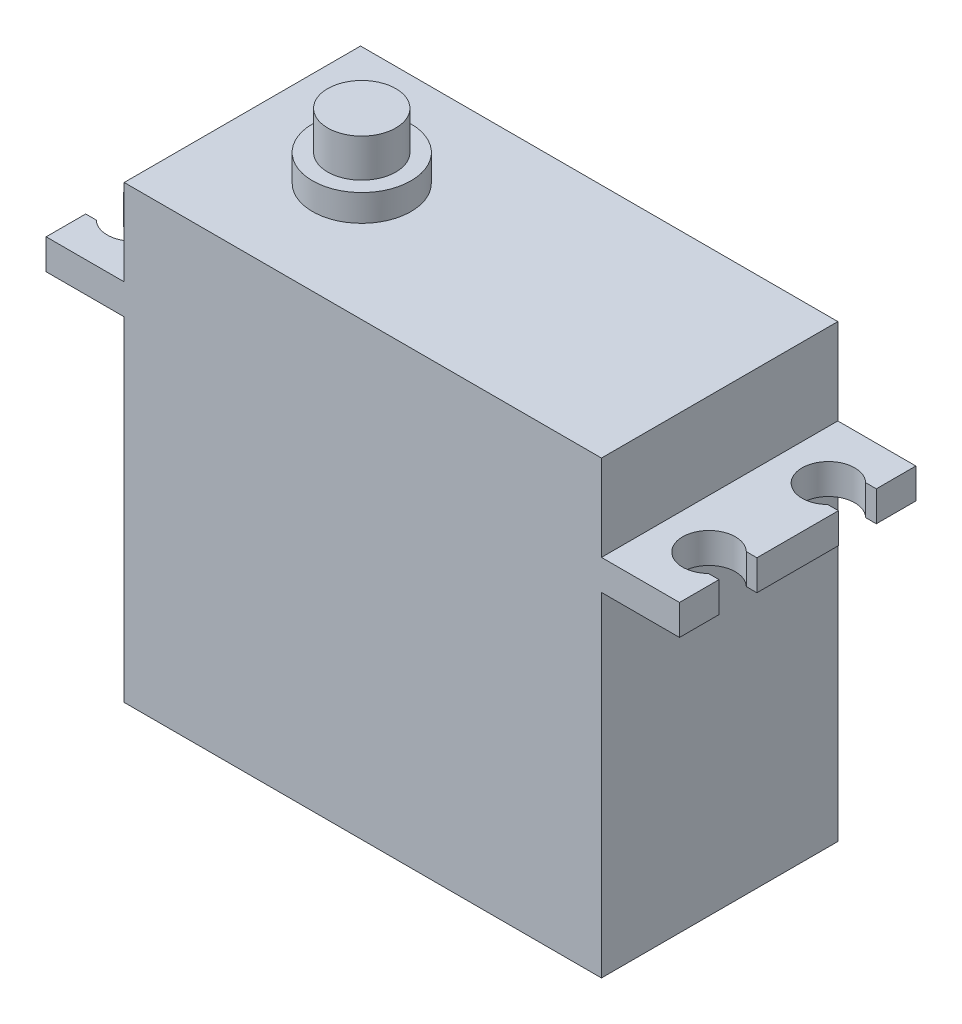
SolidWorks part; units mm, degrees
ref_plane "Front Plane" through (0, 0, 0) normal (0, 0, 1) x (1, 0, 0)
ref_plane "Top Plane" through (0, 0, 0) normal (0, 1, 0) x (1, 0, 0)
ref_plane "Right Plane" through (0, 0, 0) normal (1, 0, 0) x (0, 0, -1)
sketch "Sketch1" plane through (0, 0, 0) normal (0, 1, 0) x (1, 0, 0)
  line L1 (0, 0) -> (40.005, 0)
  line L2 (0, 0) -> (0, 19.812)
  line L3 (0, 19.812) -> (40.005, 19.812)
  line L4 (40.005, 0) -> (40.005, 19.812)
  dimension "D1" = 19.812
  dimension "D2" = 40.005
extrude "Boss-Extrude1" add sketch "Sketch1" along normal blind 37.7444
sketch "Sketch2" plane through (0, 37.7444, 0) normal (0, 1, 0) x (1, 0, 0)
  line L0 (0, 9.906) -> (10.0076, 9.906) construction
  line L1 (0, 19.812) -> (0, 0) construction
  circle A0 centre (10.0076, 9.906) radius 4.1275
  dimension "D2" = 8.255
  dimension "D1" = 10.0076
extrude "Boss-Extrude2" add sketch "Sketch2" along normal blind 2.2352
sketch "Sketch3" plane through (0, 39.9796, 0) normal (0, 1, 0) x (1, 0, 0)
  circle A0 centre (10.0076, 9.906) radius 2.8575
  dimension "D1" = 5.715
extrude "Boss-Extrude3" add sketch "Sketch3" along normal blind 3.2004
sketch "Sketch4" plane through (0, 0, 0) normal (0, -1, 0) x (1, 0, 0)
  line L0 (20.0025, 0) -> (20.0025, -19.812) construction
  line L1 (0, 0) -> (40.005, 0) construction
  line L2 (40.005, -19.812) -> (0, -19.812) construction
  line L3 (0, -9.906) -> (-6.5405, -9.906) construction
  line L4 (0, 0) -> (-6.5405, 0)
  line L5 (0, 0) -> (0, -19.812)
  line L6 (0, -19.812) -> (-6.5405, -19.812)
  line L7 (-6.5405, 0) -> (-6.5405, -3.3147)
  line L8 (-6.5405, -3.3147) -> (-5.652, -3.3147)
  line L9 (-6.5405, -16.4973) -> (-5.652, -16.4973)
  line L10 (-6.5405, -6.4897) -> (-5.652, -6.4897)
  line L11 (-6.5405, -6.4897) -> (-6.5405, -13.3223)
  line L12 (-6.5405, -13.3223) -> (-5.652, -13.3223)
  line L13 (-6.5405, -16.4973) -> (-6.5405, -19.812)
  line L14 (40.005, -9.906) -> (46.5455, -9.906) construction
  line L15 (46.5455, -16.4973) -> (46.5455, -19.812)
  line L16 (46.5455, -13.3223) -> (45.657, -13.3223)
  line L17 (46.5455, -6.4897) -> (46.5455, -13.3223)
  line L18 (46.5455, -6.4897) -> (45.657, -6.4897)
  line L19 (46.5455, -16.4973) -> (45.657, -16.4973)
  line L20 (46.5455, -3.3147) -> (45.657, -3.3147)
  line L21 (46.5455, 0) -> (46.5455, -3.3147)
  line L22 (40.005, -19.812) -> (46.5455, -19.812)
  line L23 (40.005, 0) -> (40.005, -19.812)
  line L24 (40.005, 0) -> (46.5455, 0)
  arc A0 (-5.652, -6.4897) -> (-5.652, -3.3147) centre (-4.1148, -4.9022) ccw
  arc A1 (-5.652, -13.3223) -> (-5.652, -16.4973) centre (-4.1148, -14.9098) cw
  arc A2 (45.657, -13.3223) -> (45.657, -16.4973) centre (44.1198, -14.9098) ccw
  arc A3 (45.657, -6.4897) -> (45.657, -3.3147) centre (44.1198, -4.9022) cw
  dimension "D4" = 4.4196
  dimension "D1" = 53.086
  dimension "D2" = 10.0076
  dimension "D3" = 48.2346
  dimension "D5" = 3.175
extrude "Boss-Extrude4" add sketch "Sketch4" against normal blind 2.54 from offset 27.9908
